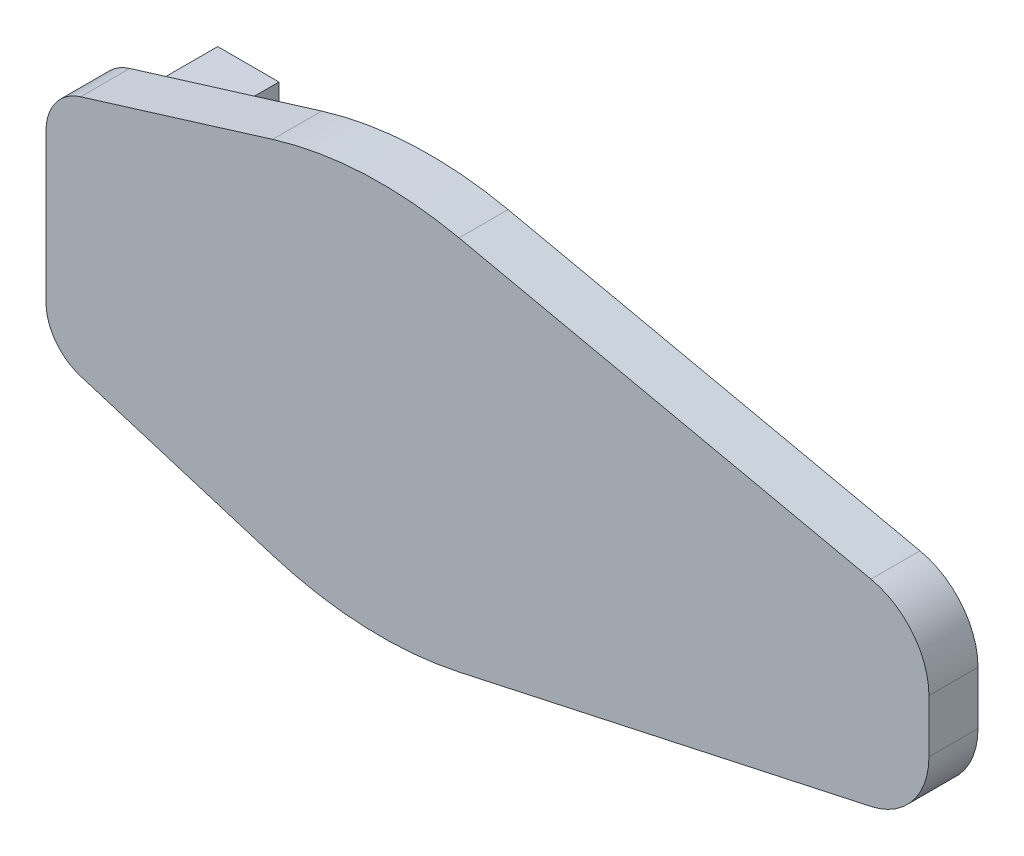
SolidWorks part; units mm, degrees
ref_plane "Front" through (0, 0, 0) normal (0, 0, 1) x (1, 0, 0)
ref_plane "Top" through (0, 0, 0) normal (0, 1, 0) x (1, 0, 0)
ref_plane "Right" through (0, 0, 0) normal (1, 0, 0) x (0, 0, -1)
sketch "Sketch1" plane through (0, 0, 0) normal (0, 0, 1) x (1, 0, 0)
  line L0 (2.8237, 9.8688) -> (18.4864, 14.6881)
  line L1 (33.6818, 15.33) -> (67.2746, 8.0273)
  line L2 (72, 2.1642) -> (72, -2.1642)
  line L3 (0, 6.0457) -> (0, -6.0457)
  line L4 (0, 0) -> (72, 0) construction
  line L5 (33.6818, -15.33) -> (67.2746, -8.0273)
  line L6 (2.8237, -9.8688) -> (18.4864, -14.6881)
  arc A0 (33.6818, 15.33) -> (18.4864, 14.6881) centre (27.3089, -13.9853) ccw
  arc A1 (67.2746, 8.0273) -> (72, 2.1642) centre (66, 2.1642) cw
  arc A2 (2.8237, 9.8688) -> (0, 6.0457) centre (4, 6.0457) ccw
  arc A3 (2.8237, -9.8688) -> (0, -6.0457) centre (4, -6.0457) cw
  arc A4 (67.2746, -8.0273) -> (72, -2.1642) centre (66, -2.1642) ccw
  arc A5 (33.6818, -15.33) -> (18.4864, -14.6881) centre (27.3089, 13.9853) cw
  point P8 (26, 17)
  point P11 (72, 7)
  point P14 (0, 9)
  dimension "D6" = 30
  dimension "D7" = 6
  dimension "D8" = 4
  dimension "D1" = 17
  dimension "D2" = 72
  dimension "D3" = 26
  dimension "D4" = 7
  dimension "D5" = 9
extrude "Boss-Extrude1" add sketch "Sketch1" along normal blind 4
sketch "Sketch2" plane through (0, 0, 0) normal (0, 0, -1) x (-1, 0, 0)
  line L1 (-5, -5) -> (0, -5)
  line L2 (-5, -5) -> (-5, 5)
  line L3 (-5, 5) -> (0, 5)
  line L4 (0, -5) -> (0, 5)
  line L5 (-5, -5) -> (0, 5) construction
  line L6 (-5, 5) -> (0, -5) construction
  point P0 (-2.5, 0)
  point P5 (0, 0)
  dimension "D1" = 10
  dimension "D2" = 5
  dimension "D3" = 0
extrude "Boss-Extrude2" add sketch "Sketch2" along normal blind 10
sketch "Sketch3" plane through (5, 0, 0) normal (1, 0, 0) x (0, 0, -1)
  line L0 (0, -5) -> (10, 5) construction
  circle A0 centre (5, 0) radius 1.55
  dimension "D1" = 3.1
extrude "Cut-Extrude1" cut sketch "Sketch3" against normal up to next
